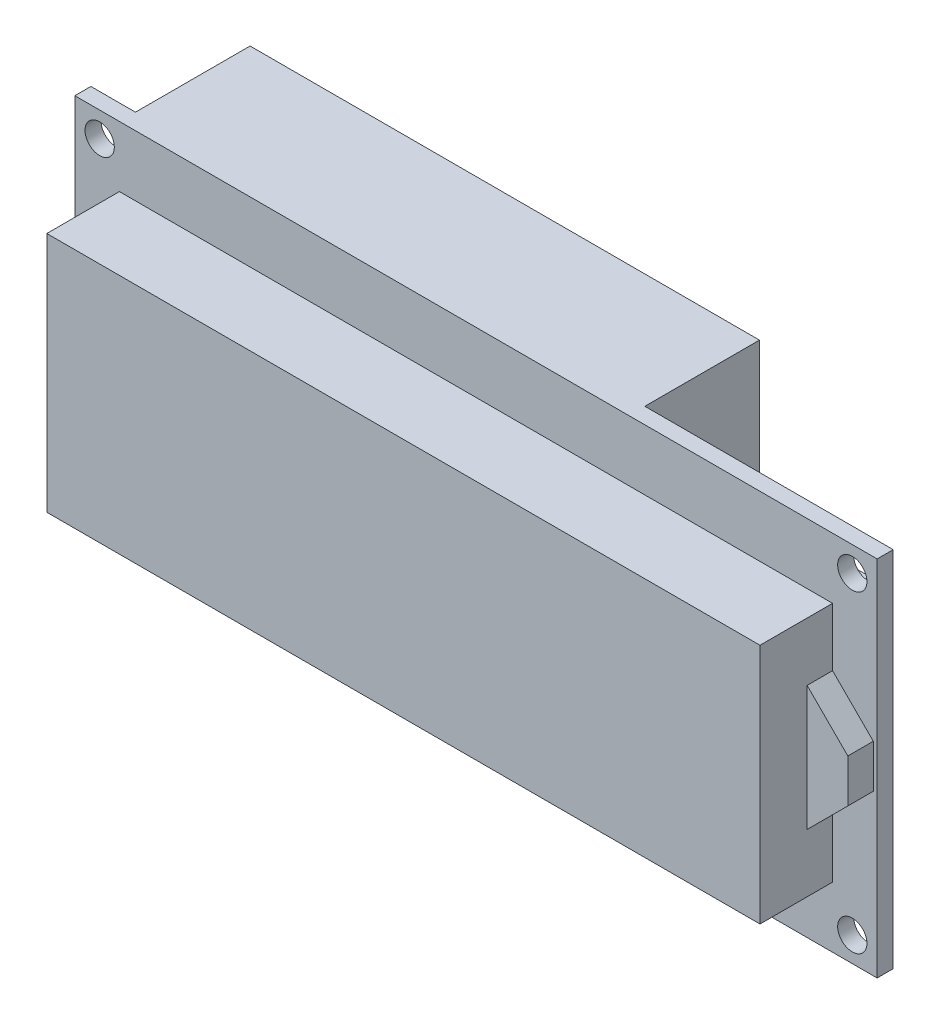
SolidWorks part; units mm, degrees
ref_plane "Front Plane" through (0, 0, 0) normal (0, 0, 1) x (1, 0, 0)
ref_plane "Top Plane" through (0, 0, 0) normal (0, 1, 0) x (1, 0, 0)
ref_plane "Right Plane" through (0, 0, 0) normal (1, 0, 0) x (0, 0, -1)
sketch "Sketch2" plane through (0, 0, 0) normal (0, 0, 1) x (1, 0, 0)
  line L1 (-40.005, 18.0975) -> (40.005, 18.0975)
  line L2 (-40.005, 18.0975) -> (-40.005, -18.0975)
  line L3 (-40.005, -18.0975) -> (40.005, -18.0975)
  line L4 (40.005, 18.0975) -> (40.005, -18.0975)
  line L5 (-40.005, 18.0975) -> (40.005, -18.0975) construction
  line L6 (-40.005, -18.0975) -> (40.005, 18.0975) construction
  point P0 (0, 0)
  dimension "D1" = 80.01
  dimension "D2" = 36.195
extrude "Boss-Extrude1" add sketch "Sketch2" along normal blind 1.6002 contours L2 L1 L4 L3
sketch "Sketch3" plane through (0, 0, 1.6002) normal (0, 0, 1) x (1, 0, 0)
  line L1 (-35.56, 12.0396) -> (35.56, 12.0396)
  line L2 (-35.56, 12.0396) -> (-35.56, -12.0396)
  line L3 (-35.56, -12.0396) -> (35.56, -12.0396)
  line L4 (35.56, 12.0396) -> (35.56, -12.0396)
  line L5 (-35.56, 12.0396) -> (35.56, -12.0396) construction
  line L6 (-35.56, -12.0396) -> (35.56, 12.0396) construction
  point P0 (0, 0)
  dimension "D1" = 71.12
  dimension "D2" = 24.0792
extrude "Boss-Extrude2" add sketch "Sketch3" along normal blind 7.239
sketch "Sketch4" plane through (0, 0, 1.6002) normal (0, 0, 1) x (1, 0, 0)
  line L0 (-40.005, 18.0975) -> (-40.005, -18.0975) construction
  line L1 (-40.005, 18.0975) -> (40.005, 18.0975) construction
  line L2 (0, 0) -> (0, 10.2067) construction
  line L3 (0, 0) -> (7.3291, 0) construction
  circle A0 centre (-37.5285, 15.621) radius 1.4605
  circle A1 centre (37.5285, 15.621) radius 1.4605
  circle A2 centre (37.5285, -15.621) radius 1.4605
  circle A3 centre (-37.5285, -15.621) radius 1.4605
  dimension "D1" = 2.921
  dimension "D2" = 1.016
  dimension "D3" = 1.016
extrude "Cut-Extrude1" cut sketch "Sketch4" against normal up to vertex (1.6002 mm away)
sketch "Sketch5" plane through (0, 0, 1.6002) normal (0, 0, 1) x (1, 0, 0)
  line L0 (35.56, 0) -> (38.4212, 0) construction
  line L1 (35.56, -12.0396) -> (35.56, 12.0396) construction
  line L2 (35.56, 6.223) -> (39.624, 2.159)
  line L3 (35.56, -12.0396) -> (35.56, 12.0396) construction
  line L4 (35.56, -6.223) -> (39.624, -2.159)
  line L5 (39.624, 2.159) -> (39.624, -2.159)
  line L6 (35.56, 6.223) -> (35.56, -6.223)
  dimension "D1" = 6.223
  dimension "D2" = 2.159
  dimension "D3" = 4.064
extrude "Boss-Extrude3" add sketch "Sketch5" along normal blind 2.54
sketch "Sketch6" plane through (0, 0, 0) normal (0, 0, -1) x (-1, 0, 0)
  line L0 (40.005, 18.0975) -> (-40.005, 18.0975) construction
  line L1 (-35.56, 12.065) -> (35.56, 12.065)
  line L2 (-35.56, 12.065) -> (-35.56, -12.065)
  line L3 (-35.56, -12.065) -> (35.56, -12.065)
  line L4 (35.56, 12.065) -> (35.56, -12.065)
  line L5 (-35.56, 12.065) -> (35.56, -12.065) construction
  line L6 (-35.56, -12.065) -> (35.56, 12.065) construction
  line L7 (-15.24, 18.0975) -> (35.56, 18.0975)
  line L8 (-15.24, 18.0975) -> (-15.24, -1.7145)
  line L9 (-15.24, -1.7145) -> (35.56, -1.7145)
  line L10 (35.56, 18.0975) -> (35.56, -1.7145)
  point P0 (0, 0)
  line M15 (40.005, 18.0975) -> (-40.005, 18.0975)
  dimension "D1" = 71.12
  dimension "D2" = 24.13
  dimension "D3" = 50.8
  dimension "D4" = 19.812
extrude "Boss-Extrude5" add sketch "Sketch6" along normal blind 2.54 contours L10 L8 L1 M15 | L8 L9 L4 L1 | L9 L8 L1 L2 L3 L4
sketch "Sketch9" plane through (0, 0, -2.54) normal (0, 0, -1) x (-1, 0, 0)
  line L0 (35.56, 18.0975) -> (35.56, -12.065) construction
  line L1 (-15.24, 18.0975) -> (35.56, 18.0975)
  line L2 (-15.24, 18.0975) -> (-15.24, -1.7145)
  line L3 (-15.24, -1.7145) -> (35.56, -1.7145)
  line L4 (35.56, 18.0975) -> (35.56, -1.7145)
  dimension "D1" = 19.812
extrude "Boss-Extrude6" add sketch "Sketch9" along normal blind 8.89
